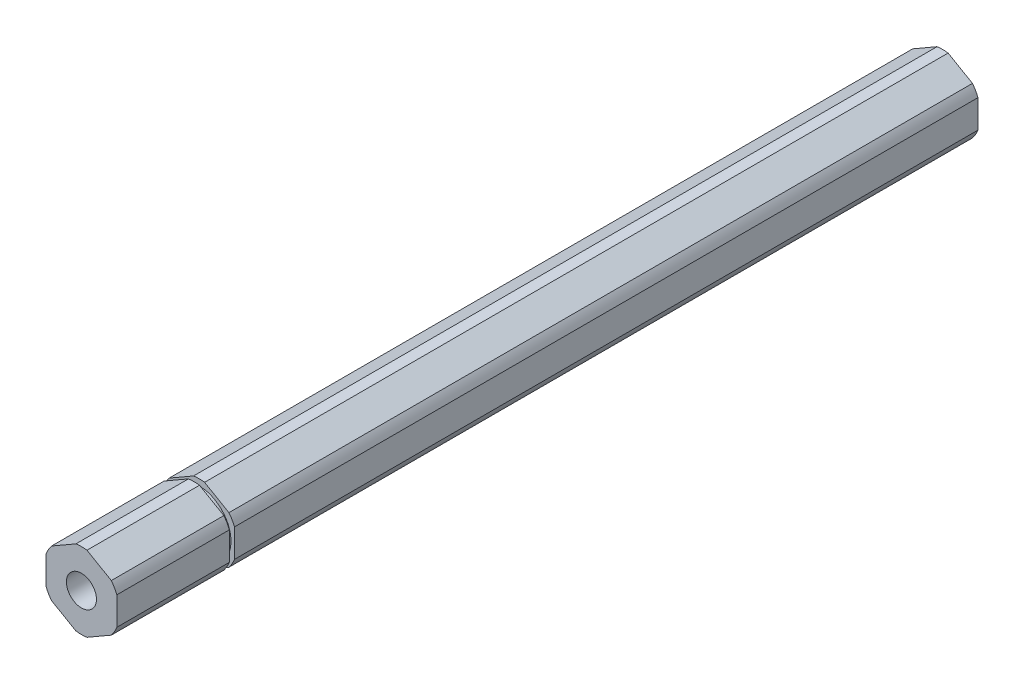
SolidWorks part; units mm, degrees
material "7075-T6 (SN)"
ref_plane "Front Plane" through (0, 0, 0) normal (0, 0, 1) x (1, 0, 0)
ref_plane "Top Plane" through (0, 0, 0) normal (0, 1, 0) x (1, 0, 0)
ref_plane "Right Plane" through (0, 0, 0) normal (1, 0, 0) x (0, 0, -1)
sketch "Sketch1" plane through (0, 0, 0) normal (0, 0, 1) x (1, 0, 0)
  line L1 (4.7625, 2.7496) -> (0, 5.4993)
  line L2 (0, 5.4993) -> (-4.7625, 2.7496)
  line L3 (-4.7625, 2.7496) -> (-4.7625, -2.7496)
  line L4 (-4.7625, -2.7496) -> (0, -5.4993)
  line L5 (0, -5.4993) -> (4.7625, -2.7496)
  line L6 (4.7625, -2.7496) -> (4.7625, 2.7496)
  circle A0 centre (0, 0) radius 4.7625 construction
  circle A1 centre (0, 0) radius 5.1245
  dimension "D1" = 10.2489
  dimension "D2" = 9.525
extrude "Boss-Extrude1" add sketch "Sketch1" along normal mid plane 115.7605 contours L6 A1 L1 L2 L3 L4 L5
sketch "Sketch2" plane through (0, 0, -57.8803) normal (0, 0, -1) x (-1, 0, 0)
  circle A0 centre (0, 0) radius 2.0193
  dimension "D1" = 4.0386
extrude "Cut-Extrude1" cut sketch "Sketch2" against normal blind 19.05
mirror "Mirror1" about plane through (0, 0, 0) normal (0, 0, 1) of "Cut-Extrude1"
sketch "Sketch3" plane through (2.3812, 4.1244, 0) normal (0.5, 0.866, 0) x (0.866, -0.5, 0)
  line L0 (0, 57.8803) -> (0, -24.7205) construction
  line L2 (1.8917, 57.8803) -> (-1.8917, 57.8803) construction
  dimension "D1" = 82.6008
ref_plane "Plane1" through (0, 0, 42.0687) normal (0, 0, -1) x (-1, 0, 0)
sketch "Sketch4" plane through (0, 0, 42.0687) normal (0, 0, -1) x (-1, 0, 0)
  circle A0 centre (0, 0) radius 4.2926
  circle A1 centre (0, 0) radius 6.35
  dimension "D1" = 8.5852
  dimension "D2" = 12.7
extrude "Cut-Extrude2" cut sketch "Sketch4" against normal blind 0.6858
